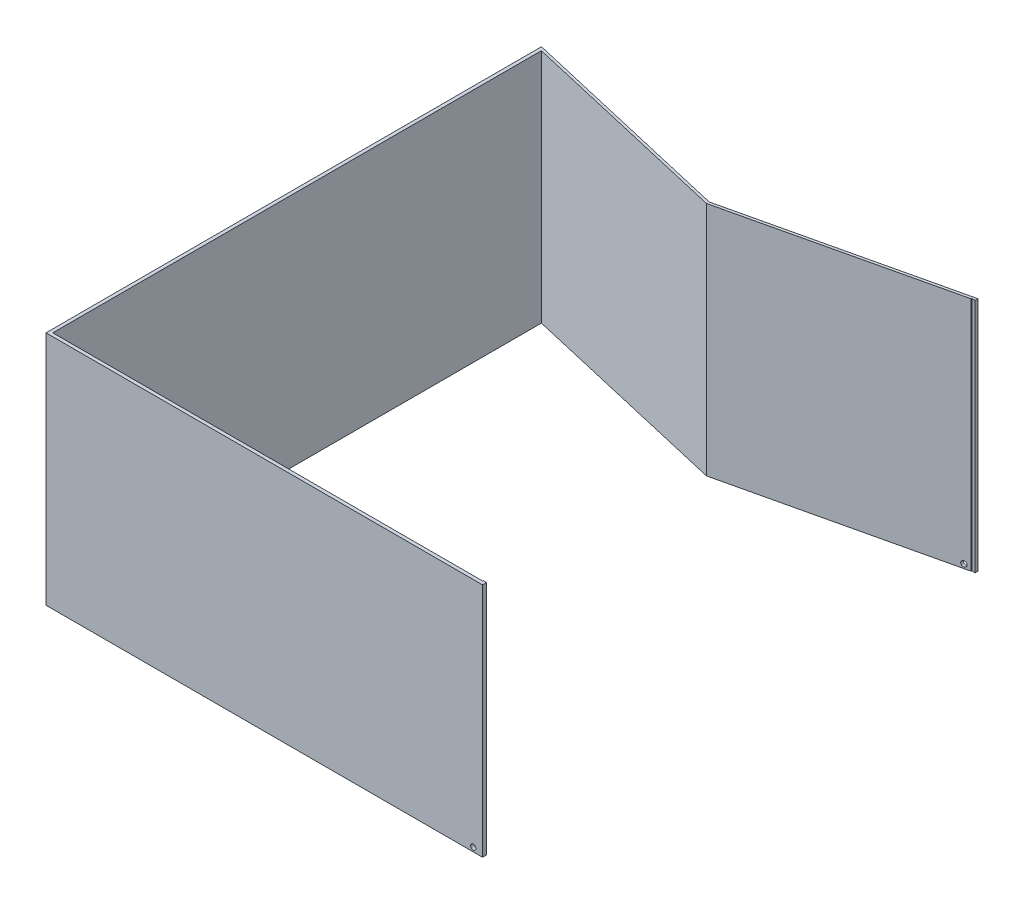
SolidWorks part; units mm, degrees
ref_plane "Front Plane" through (0, 0, 0) normal (0, 0, 1) x (1, 0, 0)
ref_plane "Top Plane" through (0, 0, 0) normal (0, 1, 0) x (1, 0, 0)
ref_plane "Right Plane" through (0, 0, 0) normal (1, 0, 0) x (0, 0, -1)
sketch "Sketch2" plane through (0, 0, 0) normal (0, 1, 0) x (1, 0, 0)
  line L1 (-323.85, -368.3) -> (323.85, -368.3)
  line L2 (-323.85, -368.3) -> (-323.85, 368.1599)
  line L4 (323.85, -368.3) -> (323.85, 368.1599)
  line L5 (-323.85, -368.3) -> (323.85, 368.3) construction
  line L6 (-323.85, 368.3) -> (323.85, -368.3) construction
  line L7 (-328.93, -373.38) -> (328.93, -373.38)
  line L8 (-328.93, -373.38) -> (-328.93, 373.38)
  line L9 (-323.85, 368.1599) -> (0, 293.1367)
  line L10 (328.93, -373.38) -> (328.93, 373.38)
  line L11 (-328.93, -373.38) -> (328.93, 373.38) construction
  line L12 (-328.93, 373.38) -> (328.93, -373.38) construction
  line L13 (0, 293.1367) -> (323.85, 368.1599)
  line L14 (328.93, 373.38) -> (0, 297.18)
  line L15 (0, 297.18) -> (-328.93, 373.38)
  line L16 (-328.93, 373.38) -> (328.93, 373.38) construction
  line L17 (0, 0) -> (0, 373.38) construction
  point P0 (0, 0)
  point P6 (0, 0)
  dimension "D1" = 736.6
  dimension "D2" = 647.7
  dimension "D3" = 76.2
  dimension "D4" = 5.08
  dimension "D5" = 5.08
extrude "Boss-Extrude1" add sketch "Sketch2" along normal blind 355.6
ref_plane "Plane1" through (0, -419.1, 0) normal (0, -1, 0) x (-1, 0, 0)
sketch "Sketch4" plane through (0, -419.1, 0) normal (0, -1, 0) x (-1, 0, 0)
  line L0 (-240.03, 0) -> (240.03, 0) construction
  line L1 (328.93, -373.38) -> (-328.93, 373.38) construction
  line L2 (-240.03, -373.38) -> (-240.03, 352.7854)
  line L3 (328.93, 373.38) -> (-328.93, -373.38) construction
  line L4 (240.03, 352.7854) -> (240.03, -373.38)
  line L6 (328.93, -373.38) -> (-328.93, -373.38) construction
  line L7 (328.93, 373.38) -> (328.93, -373.38) construction
  line L8 (-328.93, -373.38) -> (-328.93, 373.38) construction
  line L11 (240.03, -373.38) -> (-240.03, -373.38)
  line L12 (0, 297.18) -> (328.93, 373.38) construction
  line L13 (0, 297.18) -> (240.03, 352.7854)
  line L14 (-328.93, 373.38) -> (0, 297.18) construction
  line L15 (-240.03, 352.7854) -> (0, 297.18)
  line L16 (-328.93, -373.38) -> (-328.93, 373.38) construction
  line L17 (328.93, 373.38) -> (328.93, -373.38) construction
  point P0 (0, 0)
  point P15 (0, 0)
  point P16 (0, 0)
  dimension "D1" = 88.9
sketch "Sketch5" plane through (0, 0, 0) normal (0, -1, 0) x (1, 0, 0)
  line L4 (328.93, -373.38) -> (328.93, 373.38)
  line L5 (328.93, 373.38) -> (-328.93, 373.38)
  line L6 (-328.93, 373.38) -> (-328.93, -373.38)
  line L7 (0, -297.18) -> (328.93, -373.38)
  line L8 (328.93, -373.38) -> (328.93, 373.38)
  line L9 (328.93, 373.38) -> (-328.93, 373.38)
  line L10 (-328.93, 373.38) -> (-328.93, -373.38)
  line L11 (0, -297.18) -> (328.93, -373.38)
  line L13 (-328.93, -373.38) -> (0, -297.18)
  line L14 (-328.93, -373.38) -> (0, -297.18)
  dimension "D1" = 0
sketch "Sketch8" plane through (328.93, 0, 0) normal (1, 0, 0) x (0, 0, -1)
  line L0 (-373.38, 355.6) -> (373.38, 355.6) construction
  line L1 (-367.3329, 0) -> (369.0592, 0)
  line L2 (-367.3329, 0) -> (-367.3329, 355.6)
  line L3 (-367.3329, 355.6) -> (369.0592, 355.6)
  line L4 (369.0592, 0) -> (369.0592, 355.6)
  dimension "D1" = 736.3921
  dimension "D2" = 355.6
extrude "Cut-Extrude2" cut sketch "Sketch8" against normal up to surface (5.08 mm away) up to face at (323.85, 177.8, 0.07)
sketch "Sketch12" plane through (0, 0, 373.38) normal (0, 0, 1) x (1, 0, 0)
  circle A0 centre (315.0008, 6.2975) radius 3.9624
  dimension "D1" = 7.9248
extrude "Cut-Extrude4" cut sketch "Sketch12" against normal up to surface (744.4511 mm away)
